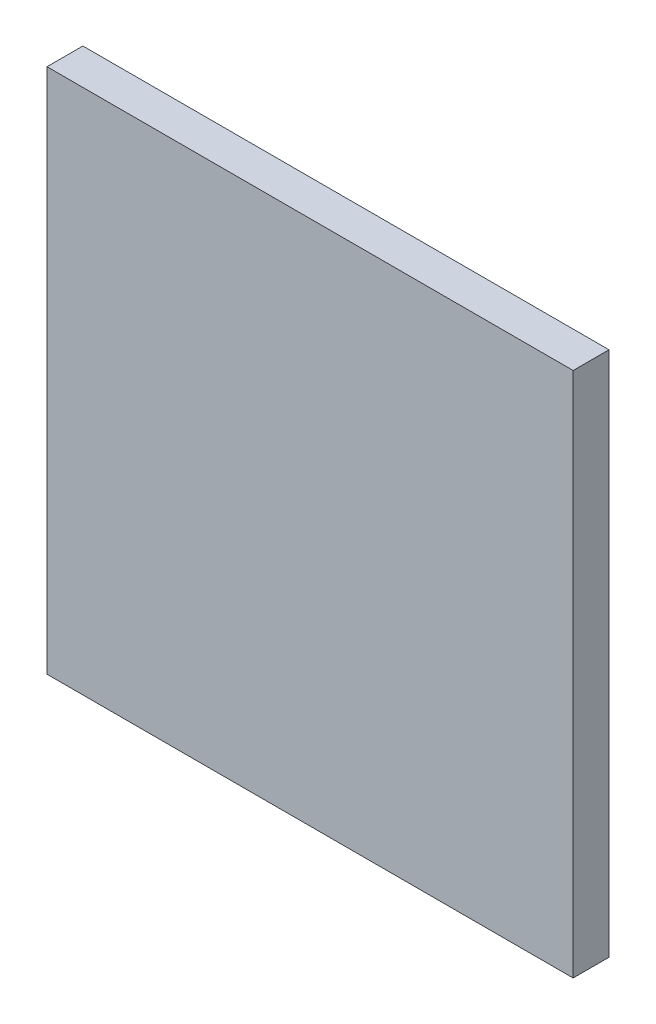
SolidWorks part; units mm, degrees
ref_plane "Front Plane" through (0, 0, 0) normal (0, 0, 1) x (1, 0, 0)
ref_plane "Top Plane" through (0, 0, 0) normal (0, 1, 0) x (1, 0, 0)
ref_plane "Right Plane" through (0, 0, 0) normal (1, 0, 0) x (0, 0, -1)
sketch "Sketch1" plane through (0, 0, 0) normal (0, 0, 1) x (1, 0, 0)
  line L1 (-11, -11) -> (11, -11)
  line L2 (-11, -11) -> (-11, 11)
  line L3 (-11, 11) -> (11, 11)
  line L4 (11, -11) -> (11, 11)
  line L5 (-11, -11) -> (11, 11) construction
  line L6 (-11, 11) -> (11, -11) construction
  point P0 (0, 0)
  dimension "D1" = 22
extrude "Boss-Extrude1" add sketch "Sketch1" along normal blind 1.5
